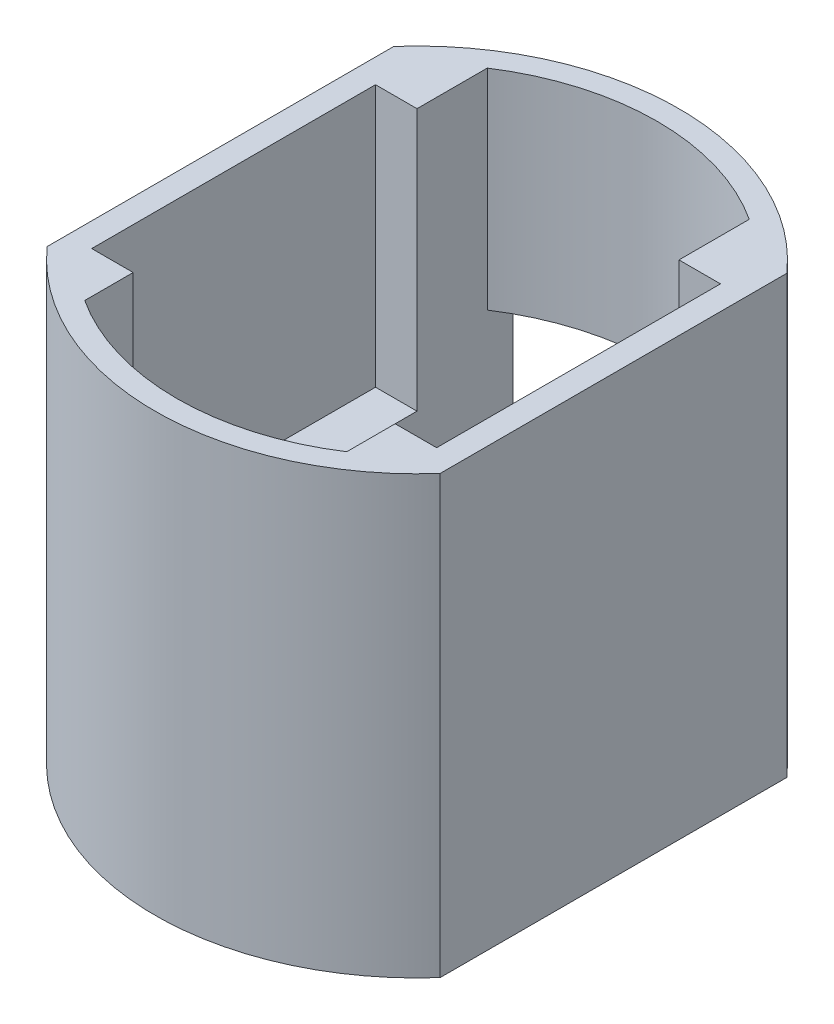
SolidWorks part; units mm, degrees
ref_plane "Front Plane" through (0, 0, 0) normal (0, 0, 1) x (1, 0, 0)
ref_plane "Top Plane" through (0, 0, 0) normal (0, 1, 0) x (1, 0, 0)
ref_plane "Right Plane" through (0, 0, 0) normal (1, 0, 0) x (0, 0, -1)
sketch "Sketch1" plane through (0, 0, 0) normal (0, 1, 0) x (1, 0, 0)
  circle A0 centre (0, 0) radius 76.2
  dimension "D1" = 152.4
extrude "Boss-Extrude1" add sketch "Sketch1" along normal blind 127
sketch "Sketch2" plane through (0, 127, 0) normal (0, 1, 0) x (1, 0, 0)
  line L2 (38.1, -58.5441) -> (38.1, 58.5441)
  line L4 (-38.1, -58.5441) -> (-38.1, 58.5441)
  arc A0 (38.1, 58.5441) -> (-38.1, 58.5441) centre (0, 0) ccw
  arc A1 (-38.1, -58.5441) -> (38.1, -58.5441) centre (0, 0) ccw
  dimension "D1" = 139.7
  dimension "D2" = 76.2
extrude "Cut-Extrude1" cut sketch "Sketch2" against normal blind 76.2
sketch "Sketch3" plane through (0, 0, 0) normal (0, -1, 0) x (1, 0, 0)
  line L0 (-38.1, 65.9911) -> (-38.1, -65.9911)
  line L1 (38.1, 65.9911) -> (38.1, -65.9911)
  line L2 (38.1, 23.1618) -> (-38.1, 23.1618)
  line L3 (38.1, -65.9911) -> (-38.1, -65.9911) construction
  circle A0 centre (0, 0) radius 76.2 construction
  arc A1 (-38.1, 65.9911) -> (38.1, 65.9911) centre (0, 0) cw
  arc A2 (-38.1, -65.9911) -> (38.1, -65.9911) centre (0, 0) ccw
  circle M5 centre (0, 0) radius 76.2
  dimension "D1" = 38.1
  dimension "D2" = 38.1
  dimension "D3" = 89.1529
extrude "Cut-Extrude2" cut sketch "Sketch3" against normal blind 66.04 contours L3 L1 L2 L0 | L3 M5
sketch "Sketch5" plane through (0, 127, 0) normal (0, 1, 0) x (1, 0, 0)
  line L2 (-57.15, 50.4016) -> (-57.15, -50.4016)
  line L4 (57.15, 50.4016) -> (57.15, -50.4016)
  circle A0 centre (0, 0) radius 76.2 construction
  arc A1 (-57.15, 50.4016) -> (-57.15, -50.4016) centre (0, 0) ccw
  arc A2 (57.15, -50.4016) -> (57.15, 50.4016) centre (0, 0) ccw
  dimension "D1" = 114.3
extrude "Cut-Extrude4" cut sketch "Sketch5" against normal through all
sketch "Sketch6" plane through (0, 127, 0) normal (0, 1, 0) x (1, 0, 0)
  line L0 (50.165, 38.1) -> (50.165, -44.45)
  line L1 (50.165, 38.1) -> (-50.165, 38.1)
  line L2 (50.165, -44.45) -> (-50.165, -44.45)
  line L3 (-50.165, 38.1) -> (-50.165, -44.45)
  arc A0 (38.1, 58.5441) -> (-38.1, 58.5441) centre (0, 0) ccw construction
  arc A1 (-38.1, -58.5441) -> (38.1, -58.5441) centre (0, 0) ccw construction
  point P7 (0, 69.85)
  point P8 (0, 38.1)
  point P13 (0, -69.85)
  dimension "D1" = 100.33
  dimension "D2" = 82.55
  dimension "D3" = 25.4
extrude "Cut-Extrude6" cut sketch "Sketch6" against normal up to surface (76.2 mm away) up to face at (0, 50.8, 43.6794)
